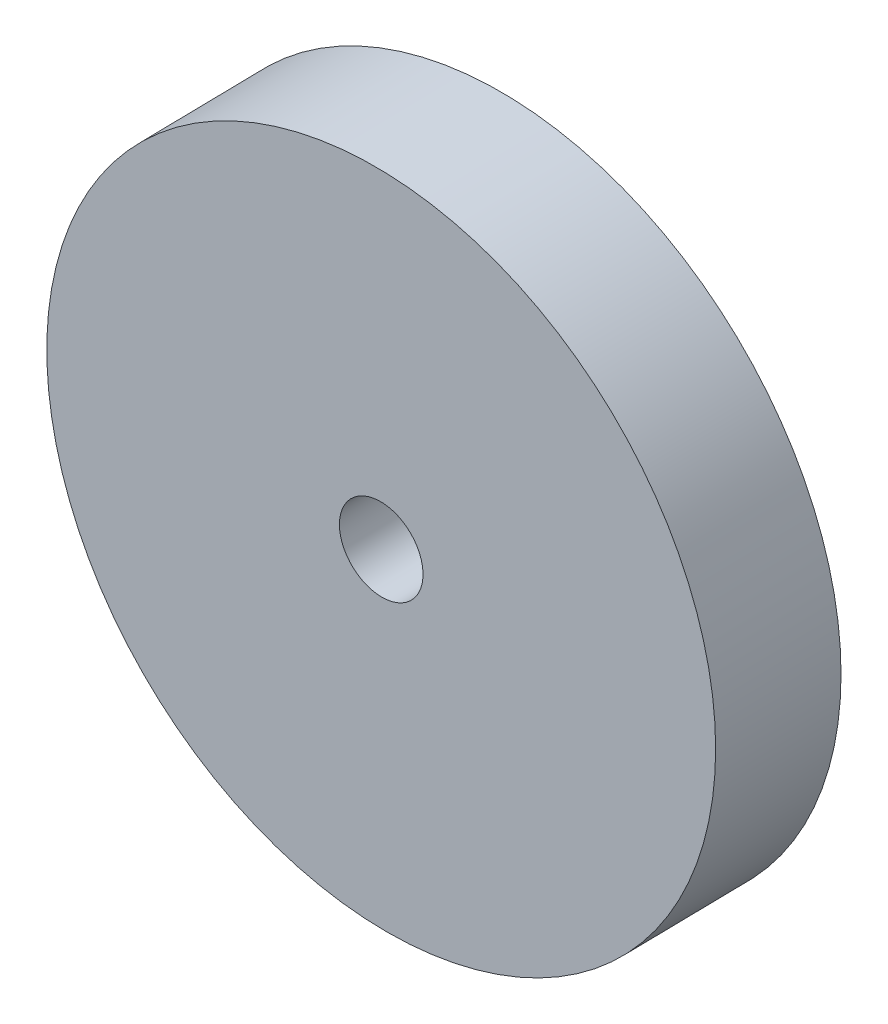
SolidWorks part; units mm, degrees
material "Brass"
ref_plane "Front Plane" through (0, 0, 0) normal (0, 0, 1) x (1, 0, 0)
ref_plane "Top Plane" through (0, 0, 0) normal (0, 1, 0) x (1, 0, 0)
ref_plane "Right Plane" through (0, 0, 0) normal (1, 0, 0) x (0, 0, -1)
sketch "Sketch1" plane through (0, 0, 0) normal (0, 1, 0) x (1, 0, 0)
  circle A0 centre (0, 0) radius 8
  circle A1 centre (0, 0) radius 1
extrude "Boss-Extrude1" add sketch "Sketch1" along normal blind 3
move or copy body "Body-Move/Copy1" bodies to move or copy 101 copy no rotation origin (0, 1.5, 0) rotation axis (1, 0, 0) rotation angle 91
